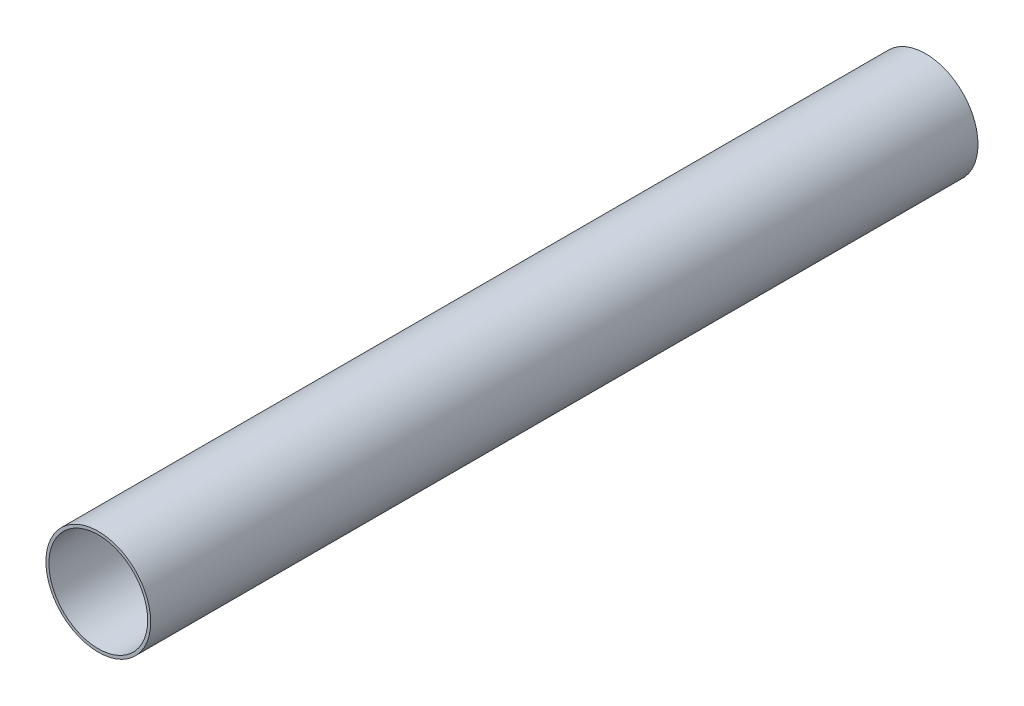
SolidWorks part; units mm, degrees
ref_plane "Front Plane" through (0, 0, 0) normal (0, 0, 1) x (1, 0, 0)
ref_plane "Top Plane" through (0, 0, 0) normal (0, 1, 0) x (1, 0, 0)
ref_plane "Right Plane" through (0, 0, 0) normal (1, 0, 0) x (0, 0, -1)
sketch "Sketch2" plane through (0, 0, 0) normal (0, 0, 1) x (1, 0, 0)
  circle A0 centre (0, 0) radius 44.1325
  circle A1 centre (0, 0) radius 41.5925
  dimension "D1" = 88.265
  dimension "D2" = 2.54
extrude "Boss-Extrude1" add sketch "Sketch2" along normal blind 696.976
